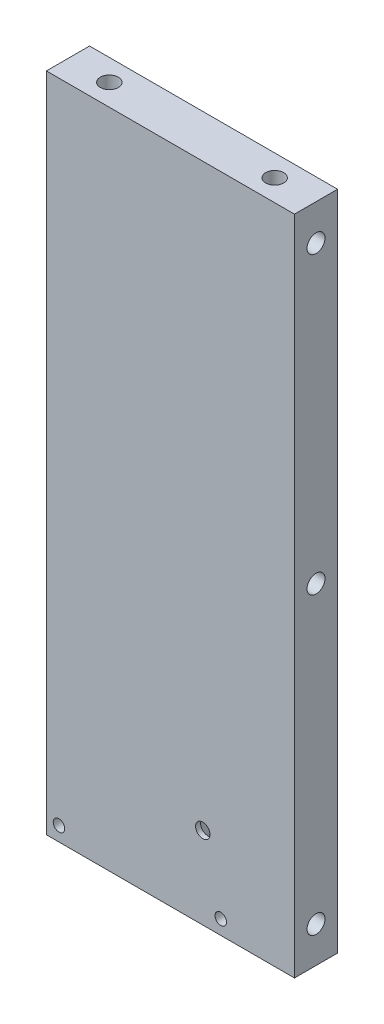
SolidWorks part; units mm, degrees
material "POM Ацеталь кополимер"
ref_plane "Front" through (0, 0, 0) normal (0, 0, 1) x (1, 0, 0)
ref_plane "Top" through (0, 0, 0) normal (0, 1, 0) x (1, 0, 0)
ref_plane "Right" through (0, 0, 0) normal (1, 0, 0) x (0, 0, -1)
sketch "Эскиз1" plane through (0, 0, 0) normal (0, 0, 1) x (1, 0, 0)
  line L1 (-17.25, 46) -> (17.25, 46)
  line L2 (-17.25, 46) -> (-17.25, -46)
  line L3 (-17.25, -46) -> (17.25, -46)
  line L4 (17.25, 46) -> (17.25, -46)
  line L5 (-17.25, 46) -> (17.25, -46) construction
  line L6 (-17.25, -46) -> (17.25, 46) construction
  point P0 (0, 0)
  dimension "D1" = 92
  dimension "D2" = 34.5
extrude "База" add sketch "Эскиз1" along normal blind 6
hole_wizard "Сторона-1-M3" positions "Эскиз4" profile "Эскиз5" tap size "M3" standard "ISO"
sketch "Эскиз4" plane through (17.25, 0, 0) normal (1, 0, 0) x (0, 0, -1)
  line L0 (-3, 0) -> (0, 0) construction
  line L1 (0, -46) -> (0, 46) construction
  line L4 (-3, 0) -> (-6, 0) construction
  line L5 (-6, -46) -> (-6, 46) construction
  line L8 (-3, 0) -> (-3, 41) construction
  line L11 (-3, 0) -> (-3, -41) construction
  point P0 (-3, 41)
  point P2 (-3, 0)
  point P4 (-3, -41)
  dimension "D1" = 82
cosmetic thread "Отверстие резьбы1"
cosmetic thread "Отверстие резьбы2"
cosmetic thread "Отверстие резьбы3"
sketch "Эскиз5" plane through (17.25, 41, 3) normal (0, 1, 0) x (0, 0, -1)
  line L0 (0, 0) -> (0, 6.7511)
  line L1 (0, 6.7511) -> (1.25, 6)
  line L2 (1.25, 6) -> (1.25, 0)
  line L5 (1.25, 0) -> (0, 0)
  line L10 (0, 6.7511) -> (-1.25, 6) construction
  line L11 (0, -6.35) -> (0, 107.95) construction
  dimension "Диаметр сверла" = 2.5
  dimension "Глубина сверла" = 6
  dimension "Угол заточки сверла" = 118
hole_wizard "Сторона-2-M3" positions "Эскиз18" profile "Эскиз19" tap size "M3" standard "ISO"
sketch "Эскиз18" plane through (-17.25, 0, 0) normal (-1, 0, 0) x (0, 0, 1)
  point P0 (3, 0)
  point P3 (3, 41)
  point P6 (3, -41)
sketch "Эскиз19" plane through (-17.25, 0, 3) normal (0, 1, 0) x (0, 0, 1)
  line L0 (0, 0) -> (0, 6.7511)
  line L1 (0, 6.7511) -> (1.25, 6)
  line L2 (1.25, 6) -> (1.25, 0)
  line L5 (1.25, 0) -> (0, 0)
  line L10 (0, 6.7511) -> (-1.25, 6) construction
  line L11 (0, -6.35) -> (0, 107.95) construction
  dimension "Диаметр сверла" = 2.5
  dimension "Глубина сверла" = 6
  dimension "Угол заточки сверла" = 118
cosmetic thread "Отверстие резьбы13"
cosmetic thread "Отверстие резьбы14"
cosmetic thread "Отверстие резьбы15"
hole_wizard "Низ-M3" positions "Эскиз6" profile "Эскиз7" tap size "M3" standard "ISO"
sketch "Эскиз6" plane through (0, -46, 0) normal (0, -1, 0) x (-1, 0, 0)
  line L0 (11.5, -3) -> (0, -3) construction
  line L1 (0, -3) -> (-11.5, -3) construction
  line L4 (-17.25, -6) -> (-17.25, 0) construction
  point P0 (11.5, -3)
  point P2 (-11.5, -3)
  point P13 (-17.25, -3)
  dimension "D1" = 23
cosmetic thread "Отверстие резьбы4"
cosmetic thread "Отверстие резьбы5"
sketch "Эскиз7" plane through (-11.5, -46, 3) normal (1, 0, 0) x (0, 0, -1)
  line L0 (0, 0) -> (0, 6.7511)
  line L1 (0, 6.7511) -> (1.25, 6)
  line L2 (1.25, 6) -> (1.25, 0)
  line L5 (1.25, 0) -> (0, 0)
  line L10 (0, 6.7511) -> (-1.25, 6) construction
  line L11 (0, -6.35) -> (0, 107.95) construction
  dimension "Диаметр сверла" = 2.5
  dimension "Глубина сверла" = 6
  dimension "Угол заточки сверла" = 118
hole_wizard "Верх-M3" positions "Эскиз16" profile "Эскиз17" tap size "M3" standard "ISO"
sketch "Эскиз16" plane through (0, 46, 0) normal (0, 1, 0) x (1, 0, 0)
  point P0 (-11.5, -3)
  point P3 (11.5, -3)
sketch "Эскиз17" plane through (-11.5, 46, 3) normal (1, 0, 0) x (0, 0, 1)
  line L0 (0, 0) -> (0, 6.7511)
  line L1 (0, 6.7511) -> (1.25, 6)
  line L2 (1.25, 6) -> (1.25, 0)
  line L5 (1.25, 0) -> (0, 0)
  line L10 (0, 6.7511) -> (-1.25, 6) construction
  line L11 (0, -6.35) -> (0, 107.95) construction
  dimension "Диаметр сверла" = 2.5
  dimension "Глубина сверла" = 6
  dimension "Угол заточки сверла" = 118
cosmetic thread "Отверстие резьбы11"
cosmetic thread "Отверстие резьбы12"
hole_wizard "Натяжение-M6" positions "Эскиз8" profile "Эскиз9" countersink size "M6" standard "DIN" end condition through all
sketch "Эскиз8" plane through (0, 0, 0) normal (0, 0, 1) x (1, 0, 0)
  line L2 (17.25, -46) -> (17.25, 46) construction
  line L3 (-17.25, -46) -> (17.25, -46) construction
  point P0 (4.5, -34.6)
  dimension "D1" = 12.75
  dimension "D2" = 11.4
sketch "Эскиз9" plane through (4.5, -34.6, 0) normal (1, 0, 0) x (0, 1, 0)
  line L0 (0, 0) -> (0, 6)
  line L1 (0, 6) -> (1, 6)
  line L2 (1, 6) -> (1, 5.3)
  line L3 (1, 5.3) -> (6.3, 0)
  line L5 (6.3, 0) -> (0, 0)
  line L6 (-1, 5.3) -> (-6.3, 0) construction
  line L11 (0, -6.35) -> (0, 107.95) construction
  dimension "Диаметр сквозного отверстия" = 2
  dimension "Глубина сквозного отверстия" = 6
  dimension "Диаметр передней зенковки" = 12.6
  dimension "Угол передней зенковки" = 90
hole_wizard "Отверстие обработанное метчиком M21" positions "Эскиз12" profile "Эскиз13" tap size "M2" standard "DIN" end condition through all
sketch "Эскиз12" plane through (0, 0, 6) normal (0, 0, 1) x (1, 0, 0)
  line L0 (-17.25, 46) -> (-17.25, -46) construction
  line L1 (-17.25, -46) -> (17.25, -46) construction
  point P0 (-15.5, -44)
  point P3 (7, -44)
  dimension "D1" = 22.5
  dimension "D2" = 1.75
  dimension "D3" = 2
sketch "Эскиз13" plane through (-15.5, -44, 6) normal (1, 0, 0) x (0, -1, 0)
  line L0 (0, 0) -> (0, 6)
  line L1 (0, 6) -> (0.8, 6)
  line L2 (0.8, 6) -> (0.8, 0)
  line L5 (0.8, 0) -> (0, 0)
  line L11 (0, -6.35) -> (0, 107.95) construction
  dimension "Диаметр проходного сверла" = 1.6
  dimension "Глубина проходного сверла" = 6
cosmetic thread "Отверстие резьбы8"
cosmetic thread "Отверстие резьбы9"
